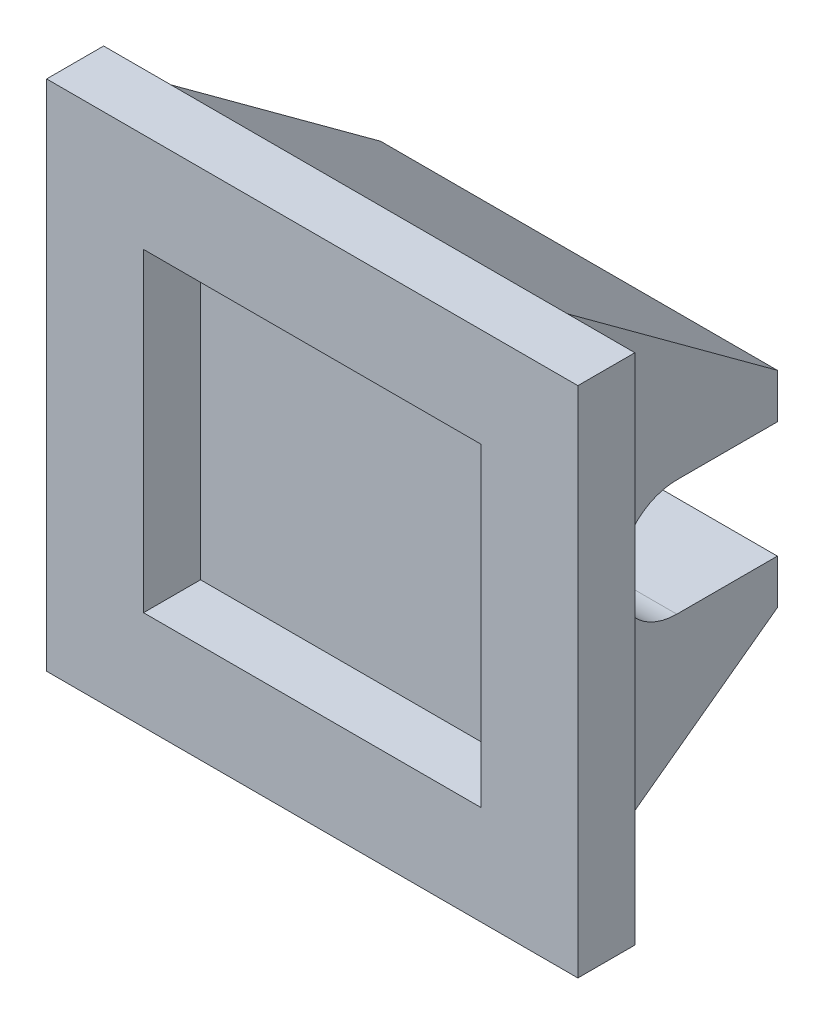
SolidWorks part; units mm, degrees
ref_plane "Front Plane" through (0, 0, 0) normal (0, 0, 1) x (1, 0, 0)
ref_plane "Top Plane" through (0, 0, 0) normal (0, 1, 0) x (1, 0, 0)
ref_plane "Right Plane" through (0, 0, 0) normal (1, 0, 0) x (0, 0, -1)
sketch "Sketch1" plane through (0, 0, 0) normal (0, 0, 1) x (1, 0, 0)
  line L1 (-14.7955, -14.2875) -> (14.7955, -14.2875)
  line L2 (-14.7955, -14.2875) -> (-14.7955, 14.2875)
  line L3 (-14.7955, 14.2875) -> (14.7955, 14.2875)
  line L4 (14.7955, -14.2875) -> (14.7955, 14.2875)
  line L5 (-14.7955, -14.2875) -> (14.7955, 14.2875) construction
  line L6 (-14.7955, 14.2875) -> (14.7955, -14.2875) construction
  point P0 (0, 0)
extrude "Boss-Extrude1" add sketch "Sketch1" along normal blind 3.175
sketch "Sketch2" plane through (0, 0, 0) normal (1, 0, 0) x (0, 0, -1)
  line L0 (0, -14.2875) -> (11.684, -5.7246)
  line L1 (11.684, -5.7246) -> (11.684, -3.2385)
  line L2 (11.684, -3.2385) -> (6.0833, -3.2385)
  line L3 (-3.175, 14.2875) -> (-3.175, -14.2875) construction
  line L5 (1.7463, 0) -> (-1.7463, 0) construction
  line L6 (11.684, 5.7246) -> (11.684, 3.2385)
  line L7 (11.684, 3.2385) -> (6.0833, 3.2385)
  line L8 (0, 14.2875) -> (11.684, 5.7246)
  line L9 (0, -14.2875) -> (0, 14.2875)
  line L10 (-3.175, -14.2875) -> (-3.175, 14.2875) construction
  arc A0 (6.0833, -3.2385) -> (6.0833, 3.2385) centre (6.0833, 0) cw
  dimension "D1" = 3.2385
  dimension "D2" = 9.2583
  dimension "D3" = 14.859
extrude "Boss-Extrude2" add sketch "Sketch2" along normal mid plane 22.098
sketch "Sketch3" plane through (0, 0, 3.175) normal (0, 0, 1) x (1, 0, 0)
  line L1 (-9.398, 8.763) -> (9.398, 8.763)
  line L2 (-9.398, 8.763) -> (-9.398, -8.763)
  line L3 (-9.398, -8.763) -> (9.398, -8.763)
  line L4 (9.398, 8.763) -> (9.398, -8.763)
  line L5 (-9.398, 8.763) -> (9.398, -8.763) construction
  line L6 (-9.398, -8.763) -> (9.398, 8.763) construction
  point P1 (0, 0)
extrude "Cut-Extrude1" cut sketch "Sketch3" against normal blind 3.175
